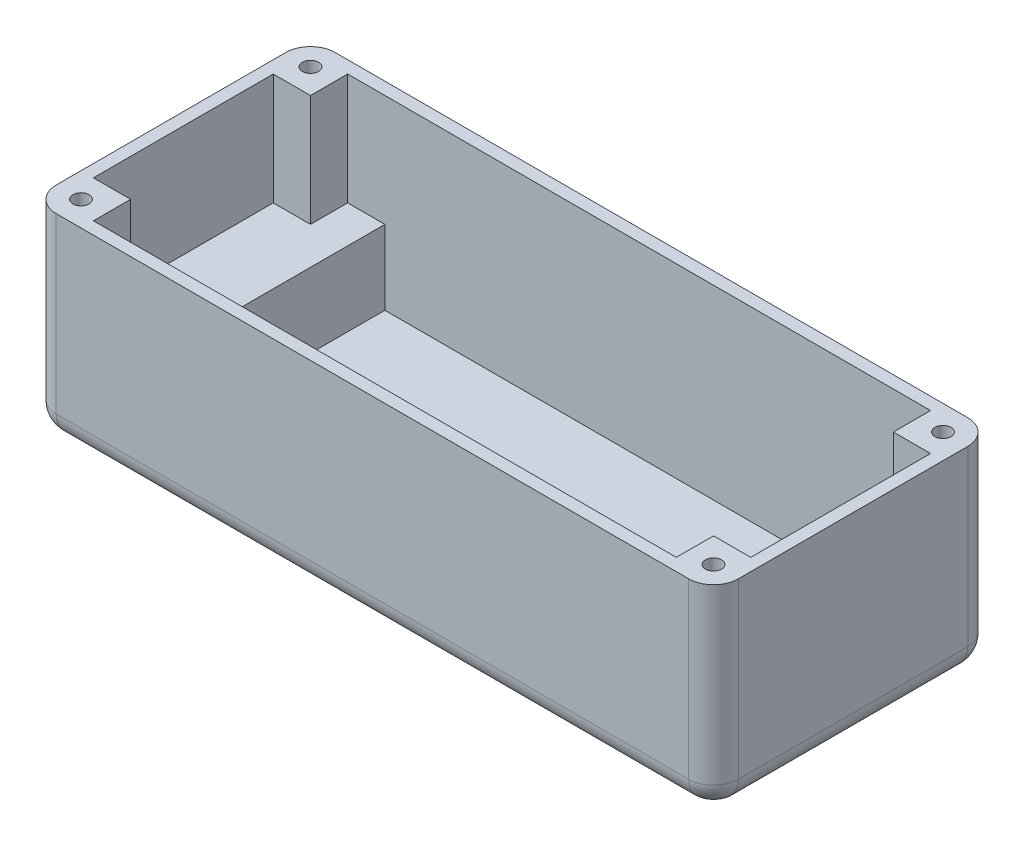
SolidWorks part; units mm, degrees
ref_plane "Front Plane" through (0, 0, 0) normal (0, 0, 1) x (1, 0, 0)
ref_plane "Top Plane" through (0, 0, 0) normal (0, 1, 0) x (1, 0, 0)
ref_plane "Right Plane" through (0, 0, 0) normal (1, 0, 0) x (0, 0, -1)
sketch "Sketch1" plane through (0, 0, 0) normal (0, 1, 0) x (1, 0, 0)
  line L1 (-55, 22.5) -> (55, 22.5)
  line L2 (-55, 22.5) -> (-55, -22.5)
  line L3 (-55, -22.5) -> (55, -22.5)
  line L4 (55, 22.5) -> (55, -22.5)
  line L5 (-55, 22.5) -> (55, -22.5) construction
  line L6 (-55, -22.5) -> (55, 22.5) construction
  point P0 (0, 0)
  dimension "D1" = 45
  dimension "D2" = 110
extrude "Boss-Extrude1" add sketch "Sketch1" along normal blind 2
sketch "Sketch3" plane through (0, 2, 0) normal (0, 1, 0) x (1, 0, 0)
  line L1 (-55, 22.5) -> (55, 22.5)
  line L2 (-55, 22.5) -> (-55, -22.5)
  line L3 (-55, -22.5) -> (55, -22.5)
  line L4 (55, 22.5) -> (55, -22.5)
  line L5 (-55, 22.5) -> (55, -22.5) construction
  line L6 (-55, -22.5) -> (55, 22.5) construction
  line L7 (-53, 20.5) -> (53, 20.5)
  line L8 (-53, 20.5) -> (-53, -20.5)
  line L9 (-53, -20.5) -> (53, -20.5)
  line L10 (53, 20.5) -> (53, -20.5)
  line L11 (-53, 20.5) -> (53, -20.5) construction
  line L12 (-53, -20.5) -> (53, 20.5) construction
  point P0 (0, 0)
  point P7 (0, 0)
  dimension "D1" = 41
  dimension "D2" = 106
extrude "Boss-Extrude2" add sketch "Sketch3" along normal blind 30
sketch "Sketch4" plane through (0, 2, 0) normal (0, 1, 0) x (1, 0, 0)
  line L0 (-53, -20.5) -> (53, -20.5) construction
  line L1 (-53, 20.5) -> (-41, 20.5)
  line L2 (-53, 20.5) -> (-53, -20.5)
  line L3 (-53, -20.5) -> (-41, -20.5)
  line L4 (-41, 20.5) -> (-41, -20.5)
  line L5 (-53, -20.5) -> (53, -20.5) construction
  line L6 (53, 20.5) -> (41, 20.5)
  line L7 (53, 20.5) -> (53, -20.5)
  line L8 (53, -20.5) -> (41, -20.5)
  line L9 (41, 20.5) -> (41, -20.5)
  dimension "D1" = 12
  dimension "D2" = 12
extrude "Boss-Extrude3" add sketch "Sketch4" along normal blind 12
sketch "Sketch5" plane through (0, 14, 0) normal (0, 1, 0) x (1, 0, 0)
  line L1 (-53, 20.5) -> (-47, 20.5)
  line L2 (-53, 20.5) -> (-53, 14.5)
  line L3 (-53, 14.5) -> (-47, 14.5)
  line L4 (-47, 20.5) -> (-47, 14.5)
  line L5 (-53, -20.5) -> (-47, -20.5)
  line L6 (-53, -20.5) -> (-53, -14.5)
  line L7 (-53, -14.5) -> (-47, -14.5)
  line L8 (-47, -20.5) -> (-47, -14.5)
  dimension "D1" = 6
  dimension "D2" = 6
  dimension "D3" = 6
  dimension "D4" = 6
extrude "Boss-Extrude4" add sketch "Sketch5" along normal blind 18
sketch "Sketch6" plane through (0, 14, 0) normal (0, 1, 0) x (1, 0, 0)
  line L1 (53, 20.5) -> (47, 20.5)
  line L2 (53, 20.5) -> (53, 14.5)
  line L3 (53, 14.5) -> (47, 14.5)
  line L4 (47, 20.5) -> (47, 14.5)
  line L5 (53, -20.5) -> (47, -20.5)
  line L6 (53, -20.5) -> (53, -14.5)
  line L7 (53, -14.5) -> (47, -14.5)
  line L8 (47, -20.5) -> (47, -14.5)
  dimension "D1" = 6
  dimension "D2" = 6
  dimension "D3" = 6
  dimension "D4" = 6
extrude "Boss-Extrude5" add sketch "Sketch6" along normal blind 18
fillet "Fillet1" radius 4 4 edges at (55, 16, -22.5) (55, 16, 22.5) (-55, 16, 22.5) (-55, 16, -22.5)
fillet "Fillet2" radius 4 8 edges at (53.8284, 0, 21.3284) (53.8284, 0, -21.3284) (55, 0, 0) (-53.8284, 0, 21.3284) (0, 0, 22.5) (-53.8284, 0, -21.3284) (-55, 0, 0) (0, 0, -22.5)
sketch "Sketch7" plane through (0, 32, 0) normal (0, 1, 0) x (1, 0, 0)
  circle A0 centre (-51, 18.5) radius 1.3
  circle A1 centre (51, 18.5) radius 1.3
  circle A2 centre (51, -18.5) radius 1.3
  circle A3 centre (-51, -18.5) radius 1.3
  dimension "D1" = 2.6
  dimension "D2" = 2.6
  dimension "D3" = 2.6
  dimension "D4" = 2.6
extrude "Cut-Extrude1" cut sketch "Sketch7" against normal blind 34
sketch "Sketch8" plane through (0, 0, 0) normal (0, -1, 0) x (1, 0, 0)
  circle A0 centre (-51, 18.5) radius 2.9
  circle A1 centre (-51, -18.5) radius 2.9
  circle A2 centre (51, -18.5) radius 2.9
  circle A3 centre (51, 18.5) radius 2.9
  dimension "D1" = 5.8
  dimension "D2" = 5.8
  dimension "D3" = 5.8
  dimension "D4" = 5.8
extrude "Cut-Extrude2" cut sketch "Sketch8" against normal blind 25
sketch "Sketch9" plane through (0, 2, 0) normal (0, 1, 0) x (1, 0, 0)
  line L1 (41, 20.5) -> (41, -20.5) construction
  line L2 (31, 10) -> (41, 10)
  line L3 (31, 10) -> (31, -10)
  line L4 (31, -10) -> (41, -10)
  line L5 (41, 10) -> (41, -10)
  line L6 (31, 10) -> (41, -10) construction
  line L7 (31, -10) -> (41, 10) construction
  line L8 (41, 20.5) -> (-41, 20.5) construction
  point P2 (36, 0)
  dimension "D1" = 20
  dimension "D2" = 10
  dimension "D3" = 0
  dimension "D4" = 10.5
extrude "Cut-Extrude3" cut sketch "Sketch9" against normal blind 10
